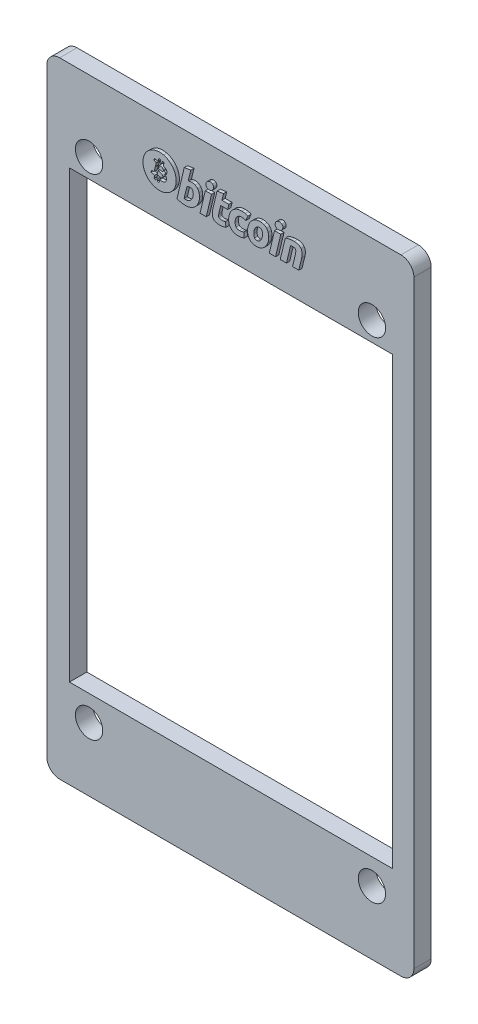
SolidWorks part; units mm, degrees
material "Plastique personnalisé"
ref_plane "Plan de face" through (0, 0, 0) normal (0, 0, 1) x (1, 0, 0)
ref_plane "Plan de dessus" through (0, 0, 0) normal (0, 1, 0) x (1, 0, 0)
ref_plane "Plan de droite" through (0, 0, 0) normal (1, 0, 0) x (0, 0, -1)
sketch "Esquisse1" plane through (0, 0, 0) normal (0, 0, 1) x (1, 0, 0)
  line L1 (-31, -51) -> (26, -51)
  line L2 (-31, -51) -> (-31, 46)
  line L3 (-31, 46) -> (26, 46)
  line L4 (26, -51) -> (26, 46)
  line L5 (-31, -51) -> (26, 46) construction
  line L6 (-31, 46) -> (26, -51) construction
  point P0 (-2.5, -2.5)
  dimension "D1" = 97
  dimension "D2" = 57
extrude "Boss.-Extru.1" add sketch "Esquisse1" along normal blind 2.7
fillet "Congé1" radius 2 4 edges at (-31, -51, 1.35) (26, -51, 1.35) (-31, 46, 1.35) (26, 46, 1.35)
sketch "Esquisse2" plane through (0, 0, 2.7) normal (0, 0, 1) x (1, 0, 0)
  line L1 (-27.4785, 31.965) -> (22.6535, 31.965)
  line L2 (-27.4785, 31.965) -> (-27.4785, -37.1836)
  line L3 (-27.4785, -37.1836) -> (22.6535, -37.1836)
  line L4 (22.6535, 31.965) -> (22.6535, -37.1836)
extrude "Enlèv. mat.-Extru.1" cut sketch "Esquisse2" against normal blind 4
sketch "Esquisse3" plane through (0, 0, 2.7) normal (0, 0, 1) x (1, 0, 0)
  circle A0 centre (-24.4301, 34.9595) radius 2.124
  circle A1 centre (19.4865, 34.9595) radius 2.124
  circle A2 centre (19.4865, -41.1389) radius 2.124
  circle A3 centre (-24.4301, -41.1389) radius 2.124
extrude "Enlèv. mat.-Extru.2" cut sketch "Esquisse3" against normal blind 4
sketch "Esquisse4" plane through (-2.3914, 35.7416, 2.7) normal (0, 0, 1) x (1, 0, 0)
  line L0 (-10.7436, 3.5103) -> (-10.6026, 4.0757)
  line L1 (-10.9703, 2.6018) -> (-10.8147, 3.2251)
  line L2 (-10.0195, 4.2739) -> (-9.9034, 4.739)
  line L3 (-9.9034, 4.739) -> (-10.1866, 4.8096)
  line L4 (-10.1866, 4.8096) -> (-10.2995, 4.3567)
  line L5 (-10.5262, 4.4101) -> (-10.4126, 4.866)
  line L6 (-10.4126, 4.866) -> (-10.6955, 4.9365)
  line L7 (-10.6955, 4.9365) -> (-10.8116, 4.4715)
  line L8 (-10.9924, 4.514) -> (-10.992, 4.5155)
  line L9 (-10.992, 4.5155) -> (-11.3825, 4.613)
  line L10 (-11.3825, 4.613) -> (-11.4578, 4.3106)
  line L11 (-11.1203, 4.0948) -> (-11.2524, 3.5649)
  line L12 (-11.2528, 3.5628) -> (-11.438, 2.8205)
  line L13 (-11.7736, 2.8046) -> (-11.9142, 2.4804)
  line L14 (-11.9142, 2.4804) -> (-11.5457, 2.3885)
  line L15 (-11.3438, 2.3365) -> (-11.4611, 1.866)
  line L16 (-11.4611, 1.866) -> (-11.1782, 1.7954)
  line L17 (-11.1782, 1.7954) -> (-11.0622, 2.261)
  line L18 (-10.8366, 2.2024) -> (-10.9522, 1.7391)
  line L19 (-10.9522, 1.7391) -> (-10.6691, 1.6686)
  line L20 (-10.6691, 1.6686) -> (-10.5519, 2.1381)
  line L21 (-6.3518, 3.2945) -> (-6.7826, 1.5051)
  line L22 (-7.8866, 0.9301) -> (-6.7567, 5.6782)
  line L23 (-6.7567, 5.6782) -> (-5.7446, 5.8351)
  line L24 (-5.7446, 5.8351) -> (-6.1491, 4.1502)
  line L25 (-3.343, 0.7663) -> (-4.3096, 0.7663)
  line L26 (-4.3096, 0.7663) -> (-3.4932, 4.2016)
  line L27 (-3.4932, 4.2016) -> (-2.52, 4.2016)
  line L28 (-2.52, 4.2016) -> (-3.343, 0.7663)
  line L29 (-1.6728, 5.0574) -> (-0.6602, 5.2143)
  line L30 (-0.6602, 5.2143) -> (-0.9089, 4.2017)
  line L31 (-0.9089, 4.2017) -> (0.1754, 4.2017)
  line L32 (0.1754, 4.2017) -> (-0.0204, 3.4051)
  line L33 (-0.0204, 3.4051) -> (-1.0982, 3.4051)
  line L34 (-1.0982, 3.4051) -> (-1.3853, 2.2034)
  line L35 (-0.3667, 1.6092) -> (-0.2945, 0.8644)
  line L36 (-2.3131, 2.3537) -> (-1.6728, 5.0574)
  line L37 (3.1375, 4.0912) -> (2.8042, 3.3331)
  line L38 (2.4909, 1.6348) -> (2.5632, 0.8577)
  line L39 (7.4135, 0.7663) -> (6.4461, 0.7663)
  line L40 (6.4461, 0.7663) -> (7.2624, 4.2016)
  line L41 (7.2624, 4.2016) -> (8.2361, 4.2016)
  line L42 (8.2361, 4.2016) -> (7.4135, 0.7663)
  line L43 (11.4737, 2.6215) -> (11.029, 0.7666)
  line L44 (11.029, 0.7666) -> (10.056, 0.7666)
  line L45 (10.056, 0.7666) -> (10.487, 2.5825)
  line L46 (9.7492, 3.4248) -> (9.1157, 0.7669)
  line L47 (9.1157, 0.7669) -> (8.1422, 0.7669)
  line L48 (8.1422, 0.7669) -> (8.9329, 4.0454)
  spline S0 degree 3 poles (-8.0865, 2.6309) (-8.4311, 1.2483) (-9.8315, 0.4071) (-11.214, 0.7517) knots 0 0 0 0 1 1 1 1
  spline S1 degree 3 poles (-11.214, 0.7517) (-12.5961, 1.0964) (-13.4376, 2.4967) (-13.0927, 3.8791) knots 0 0 0 0 1 1 1 1
  spline S2 degree 3 poles (-13.0927, 3.8791) (-12.7482, 5.2619) (-11.3479, 6.1033) (-9.9657, 5.7586) knots 0 0 0 0 1 1 1 1
  spline S3 degree 3 poles (-9.9657, 5.7586) (-8.5831, 5.4139) (-7.7419, 4.0134) (-8.0865, 2.6309) knots 0 0 0 0 1 1 1 1
  spline S4 degree 3 poles (-10.0112, 3.6278) (-10.091, 3.308) (-10.5838, 3.4705) (-10.7436, 3.5103) knots 0 0 0 0 1 1 1 1
  spline S5 degree 3 poles (-10.6026, 4.0757) (-10.4428, 4.0358) (-9.928, 3.9615) (-10.0112, 3.6278) knots 0 0 0 0 1 1 1 1
  spline S6 degree 3 poles (-10.0987, 2.7157) (-10.1862, 2.3641) (-10.7782, 2.5541) (-10.9703, 2.6018) knots 0 0 0 0 1 1 1 1
  spline S7 degree 3 poles (-10.8147, 3.2251) (-10.6228, 3.1772) (-10.0073, 3.0823) (-10.0987, 2.7157) knots 0 0 0 0 1 1 1 1
  spline S8 degree 3 poles (-9.4518, 3.6228) (-9.4004, 3.9661) (-9.6619, 4.1507) (-10.0195, 4.2739) knots 0 0 0 0 1 1 1 1
  spline S9 degree 3 poles (-10.2995, 4.3567) (-10.3739, 4.3753) (-10.4503, 4.3928) (-10.5262, 4.4101) knots 0 0 0 0 1 1 1 1
  spline S10 degree 3 poles (-10.8116, 4.4715) (-10.8732, 4.4856) (-10.9337, 4.4994) (-10.9924, 4.514) knots 0 0 0 0 1 1 1 1
  spline S11 degree 2 poles (-11.4578, 4.3106) (-11.2478, 4.2624) (-11.2523, 4.2594) knots 0 0 0 1 1 1
  spline S12 degree 3 poles (-11.2523, 4.2594) (-11.1375, 4.2308) (-11.1168, 4.1549) (-11.1203, 4.0948) knots 0 0 0 0 1 1 1 1
  spline S13 degree 3 poles (-11.2524, 3.5649) (-11.2445, 3.5628) (-11.2342, 3.5599) (-11.2229, 3.5554) knots 0 0 0 0 1 1 1 1
  spline S14 degree 3 poles (-11.2229, 3.5554) (-11.2324, 3.5578) (-11.2425, 3.5603) (-11.2528, 3.5628) knots 0 0 0 0 1 1 1 1
  spline S15 degree 3 poles (-11.438, 2.8205) (-11.452, 2.7857) (-11.4877, 2.7335) (-11.5678, 2.7532) knots 0 0 0 0 1 1 1 1
  spline S16 degree 2 poles (-11.5678, 2.7532) (-11.565, 2.7491) (-11.7736, 2.8046) knots 0 0 0 1 1 1
  spline S17 degree 3 poles (-11.5457, 2.3885) (-11.4772, 2.3713) (-11.41, 2.3534) (-11.3438, 2.3365) knots 0 0 0 0 1 1 1 1
  spline S18 degree 3 poles (-11.0622, 2.261) (-10.9849, 2.24) (-10.91, 2.2207) (-10.8366, 2.2024) knots 0 0 0 0 1 1 1 1
  spline S19 degree 3 poles (-10.5519, 2.1381) (-10.0691, 2.0467) (-9.706, 2.0836) (-9.5532, 2.5202) knots 0 0 0 0 1 1 1 1
  spline S20 degree 3 poles (-9.5532, 2.5202) (-9.43, 2.8718) (-9.5593, 3.0746) (-9.8133, 3.207) knots 0 0 0 0 1 1 1 1
  spline S21 degree 3 poles (-9.8133, 3.207) (-9.6283, 3.2497) (-9.489, 3.3714) (-9.4518, 3.6228) knots 0 0 0 0 1 1 1 1
  spline S22 degree 3 poles (-6.4564, 1.4784) (-6.304, 1.4784) (-6.1603, 1.5159) (-6.0254, 1.5895) knots 0 0 0 0 1 1 1 1
  spline S23 degree 3 poles (-6.0254, 1.5895) (-5.8902, 1.6632) (-5.7733, 1.7627) (-5.6755, 1.8866) knots 0 0 0 0 1 1 1 1
  spline S24 degree 3 poles (-5.6755, 1.8866) (-5.5777, 2.0112) (-5.5003, 2.1515) (-5.4438, 2.3083) knots 0 0 0 0 1 1 1 1
  spline S25 degree 3 poles (-5.4438, 2.3083) (-5.3874, 2.4649) (-5.3589, 2.6283) (-5.3589, 2.7983) knots 0 0 0 0 1 1 1 1
  spline S26 degree 3 poles (-5.3589, 2.7983) (-5.3589, 3.0074) (-5.3937, 3.1703) (-5.4634, 3.2882) knots 0 0 0 0 1 1 1 1
  spline S27 degree 3 poles (-5.4634, 3.2882) (-5.533, 3.4055) (-5.6617, 3.4645) (-5.8487, 3.4645) knots 0 0 0 0 1 1 1 1
  spline S28 degree 3 poles (-5.8487, 3.4645) (-5.9101, 3.4645) (-5.989, 3.4528) (-6.0869, 3.432) knots 0 0 0 0 1 1 1 1
  spline S29 degree 3 poles (-6.0869, 3.432) (-6.1852, 3.4098) (-6.2731, 3.3637) (-6.3518, 3.2945) knots 0 0 0 0 1 1 1 1
  spline S30 degree 3 poles (-6.7826, 1.5051) (-6.7567, 1.5004) (-6.7337, 1.4962) (-6.7141, 1.492) knots 0 0 0 0 1 1 1 1
  spline S31 degree 3 poles (-6.7141, 1.492) (-6.6949, 1.4875) (-6.6737, 1.4844) (-6.6526, 1.4823) knots 0 0 0 0 1 1 1 1
  spline S32 degree 3 poles (-6.6526, 1.4823) (-6.6302, 1.4798) (-6.6046, 1.4785) (-6.5737, 1.4785) knots 0 0 0 0 1 1 1 1
  spline S33 degree 3 poles (-6.5737, 1.4785) (-6.5428, 1.4785) (-6.5043, 1.4784) (-6.4564, 1.4784) knots 0 0 0 0 1 1 1 1
  spline S34 degree 3 poles (-5.6075, 4.2744) (-5.3982, 4.2744) (-5.2174, 4.2369) (-5.0654, 4.1632) knots 0 0 0 0 1 1 1 1
  spline S35 degree 3 poles (-5.0654, 4.1632) (-4.9128, 4.0889) (-4.7868, 3.9887) (-4.6858, 3.8628) knots 0 0 0 0 1 1 1 1
  spline S36 degree 3 poles (-4.6858, 3.8628) (-4.5862, 3.7362) (-4.512, 3.5882) (-4.464, 3.4186) knots 0 0 0 0 1 1 1 1
  spline S37 degree 3 poles (-4.464, 3.4186) (-4.4164, 3.2485) (-4.3925, 3.0657) (-4.3925, 2.87) knots 0 0 0 0 1 1 1 1
  spline S38 degree 3 poles (-4.3925, 2.87) (-4.3925, 2.5693) (-4.4476, 2.2853) (-4.5589, 2.0176) knots 0 0 0 0 1 1 1 1
  spline S39 degree 3 poles (-4.5589, 2.0176) (-4.6701, 1.7495) (-4.821, 1.5169) (-5.0129, 1.3184) knots 0 0 0 0 1 1 1 1
  spline S40 degree 3 poles (-5.0129, 1.3184) (-5.2047, 1.1203) (-5.4311, 0.9641) (-5.6922, 0.8487) knots 0 0 0 0 1 1 1 1
  spline S41 degree 3 poles (-5.6922, 0.8487) (-5.9529, 0.7333) (-6.2364, 0.6755) (-6.5408, 0.6755) knots 0 0 0 0 1 1 1 1
  spline S42 degree 3 poles (-6.5408, 0.6755) (-6.5801, 0.6755) (-6.6494, 0.6766) (-6.747, 0.6787) knots 0 0 0 0 1 1 1 1
  spline S43 degree 3 poles (-6.747, 0.6787) (-6.8448, 0.6806) (-6.9571, 0.6907) (-7.083, 0.7077) knots 0 0 0 0 1 1 1 1
  spline S44 degree 3 poles (-7.083, 0.7077) (-7.2095, 0.7254) (-7.3434, 0.7515) (-7.4848, 0.7866) knots 0 0 0 0 1 1 1 1
  spline S45 degree 3 poles (-7.4848, 0.7866) (-7.6261, 0.8209) (-7.7603, 0.869) (-7.8866, 0.9301) knots 0 0 0 0 1 1 1 1
  spline S46 degree 3 poles (-6.1491, 4.1502) (-6.0625, 4.1892) (-5.9753, 4.2195) (-5.8882, 4.2415) knots 0 0 0 0 1 1 1 1
  spline S47 degree 3 poles (-5.8882, 4.2415) (-5.801, 4.2631) (-5.7074, 4.2744) (-5.6075, 4.2744) knots 0 0 0 0 1 1 1 1
  spline S48 degree 3 poles (-2.8726, 4.6201) (-3.0075, 4.6201) (-3.1297, 4.6603) (-3.2384, 4.7408) knots 0 0 0 0 1 1 1 1
  spline S49 degree 3 poles (-3.2384, 4.7408) (-3.3478, 4.8208) (-3.4019, 4.9439) (-3.4019, 5.1099) knots 0 0 0 0 1 1 1 1
  spline S50 degree 3 poles (-3.4019, 5.1099) (-3.4019, 5.2012) (-3.3835, 5.2868) (-3.3467, 5.3676) knots 0 0 0 0 1 1 1 1
  spline S51 degree 3 poles (-3.3467, 5.3676) (-3.3093, 5.4483) (-3.2606, 5.5177) (-3.1994, 5.5767) knots 0 0 0 0 1 1 1 1
  spline S52 degree 3 poles (-3.1994, 5.5767) (-3.1384, 5.6353) (-3.0677, 5.682) (-2.9873, 5.7172) knots 0 0 0 0 1 1 1 1
  spline S53 degree 3 poles (-2.9873, 5.7172) (-2.9065, 5.752) (-2.8205, 5.7694) (-2.7289, 5.7694) knots 0 0 0 0 1 1 1 1
  spline S54 degree 3 poles (-2.7289, 5.7694) (-2.5941, 5.7694) (-2.4724, 5.7292) (-2.3635, 5.6487) knots 0 0 0 0 1 1 1 1
  spline S55 degree 3 poles (-2.3635, 5.6487) (-2.2549, 5.5679) (-2.2003, 5.4447) (-2.2003, 5.2796) knots 0 0 0 0 1 1 1 1
  spline S56 degree 3 poles (-2.2003, 5.2796) (-2.2003, 5.188) (-2.2188, 5.102) (-2.2559, 5.0214) knots 0 0 0 0 1 1 1 1
  spline S57 degree 3 poles (-2.2559, 5.0214) (-2.2927, 4.9408) (-2.3415, 4.8713) (-2.4027, 4.8123) knots 0 0 0 0 1 1 1 1
  spline S58 degree 3 poles (-2.4027, 4.8123) (-2.4632, 4.7537) (-2.5346, 4.707) (-2.6147, 4.6721) knots 0 0 0 0 1 1 1 1
  spline S59 degree 3 poles (-2.6147, 4.6721) (-2.6956, 4.6368) (-2.7813, 4.6201) (-2.8726, 4.6201) knots 0 0 0 0 1 1 1 1
  spline S60 degree 3 poles (-1.3853, 2.2034) (-1.4118, 2.1034) (-1.4267, 2.0099) (-1.431, 1.9229) knots 0 0 0 0 1 1 1 1
  spline S61 degree 3 poles (-1.431, 1.9229) (-1.4357, 1.8355) (-1.4247, 1.7605) (-1.3986, 1.6974) knots 0 0 0 0 1 1 1 1
  spline S62 degree 3 poles (-1.3986, 1.6974) (-1.3725, 1.6341) (-1.3258, 1.5852) (-1.2581, 1.5509) knots 0 0 0 0 1 1 1 1
  spline S63 degree 3 poles (-1.2581, 1.5509) (-1.1906, 1.5157) (-1.0941, 1.4981) (-0.9676, 1.4981) knots 0 0 0 0 1 1 1 1
  spline S64 degree 3 poles (-0.9676, 1.4981) (-0.8633, 1.4981) (-0.7616, 1.508) (-0.6634, 1.5277) knots 0 0 0 0 1 1 1 1
  spline S65 degree 3 poles (-0.6634, 1.5277) (-0.5657, 1.547) (-0.4669, 1.5739) (-0.3667, 1.6092) knots 0 0 0 0 1 1 1 1
  spline S66 degree 3 poles (-0.2945, 0.8644) (-0.425, 0.8165) (-0.5665, 0.7753) (-0.719, 0.7406) knots 0 0 0 0 1 1 1 1
  spline S67 degree 3 poles (-0.719, 0.7406) (-0.8716, 0.7054) (-1.0524, 0.6886) (-1.2612, 0.6886) knots 0 0 0 0 1 1 1 1
  spline S68 degree 3 poles (-1.2612, 0.6886) (-1.5616, 0.6886) (-1.7944, 0.7332) (-1.9602, 0.8219) knots 0 0 0 0 1 1 1 1
  spline S69 degree 3 poles (-1.9602, 0.8219) (-2.126, 0.9112) (-2.243, 1.0335) (-2.3131, 1.1882) knots 0 0 0 0 1 1 1 1
  spline S70 degree 3 poles (-2.3131, 1.1882) (-2.3823, 1.3422) (-2.4131, 1.5199) (-2.4044, 1.7201) knots 0 0 0 0 1 1 1 1
  spline S71 degree 3 poles (-2.4044, 1.7201) (-2.3956, 1.9207) (-2.3653, 2.1317) (-2.3131, 2.3537) knots 0 0 0 0 1 1 1 1
  spline S72 degree 3 poles (0.1329, 2.138) (0.1329, 2.434) (0.1808, 2.7129) (0.2765, 2.9742) knots 0 0 0 0 1 1 1 1
  spline S73 degree 3 poles (0.2765, 2.9742) (0.3721, 3.2356) (0.5097, 3.4643) (0.6883, 3.6604) knots 0 0 0 0 1 1 1 1
  spline S74 degree 3 poles (0.6883, 3.6604) (0.8663, 3.8556) (1.083, 4.0103) (1.3383, 4.1239) knots 0 0 0 0 1 1 1 1
  spline S75 degree 3 poles (1.3383, 4.1239) (1.5923, 4.2368) (1.8768, 4.2937) (2.1902, 4.2937) knots 0 0 0 0 1 1 1 1
  spline S76 degree 3 poles (2.1902, 4.2937) (2.3864, 4.2937) (2.5617, 4.2752) (2.7159, 4.238) knots 0 0 0 0 1 1 1 1
  spline S77 degree 3 poles (2.7159, 4.238) (2.8708, 4.2005) (3.0108, 4.152) (3.1375, 4.0912) knots 0 0 0 0 1 1 1 1
  spline S78 degree 3 poles (2.8042, 3.3331) (2.7171, 3.3685) (2.6267, 3.3996) (2.5332, 3.4278) knots 0 0 0 0 1 1 1 1
  spline S79 degree 3 poles (2.5332, 3.4278) (2.4397, 3.4566) (2.3254, 3.4705) (2.1904, 3.4705) knots 0 0 0 0 1 1 1 1
  spline S80 degree 3 poles (2.1904, 3.4705) (1.8677, 3.4705) (1.6127, 3.3593) (1.4229, 3.1377) knots 0 0 0 0 1 1 1 1
  spline S81 degree 3 poles (1.4229, 3.1377) (1.2336, 2.9157) (1.1384, 2.617) (1.1384, 2.2425) knots 0 0 0 0 1 1 1 1
  spline S82 degree 3 poles (1.1384, 2.2425) (1.1384, 2.0204) (1.1864, 1.841) (1.2825, 1.7036) knots 0 0 0 0 1 1 1 1
  spline S83 degree 3 poles (1.2825, 1.7036) (1.3781, 1.5663) (1.5549, 1.4979) (1.8113, 1.4979) knots 0 0 0 0 1 1 1 1
  spline S84 degree 3 poles (1.8113, 1.4979) (1.9379, 1.4979) (2.0601, 1.5112) (2.1772, 1.5369) knots 0 0 0 0 1 1 1 1
  spline S85 degree 3 poles (2.1772, 1.5369) (2.2951, 1.5631) (2.3992, 1.596) (2.4909, 1.6348) knots 0 0 0 0 1 1 1 1
  spline S86 degree 3 poles (2.5632, 0.8577) (2.4409, 0.8103) (2.306, 0.7675) (2.1582, 0.73) knots 0 0 0 0 1 1 1 1
  spline S87 degree 3 poles (2.1582, 0.73) (2.0099, 0.6938) (1.8335, 0.6749) (1.6289, 0.6749) knots 0 0 0 0 1 1 1 1
  spline S88 degree 3 poles (1.6289, 0.6749) (1.3589, 0.6749) (1.1302, 0.7145) (0.9433, 0.7923) knots 0 0 0 0 1 1 1 1
  spline S89 degree 3 poles (0.9433, 0.7923) (0.7562, 0.8713) (0.6016, 0.9763) (0.4797, 1.1091) knots 0 0 0 0 1 1 1 1
  spline S90 degree 3 poles (0.4797, 1.1091) (0.3572, 1.2423) (0.2694, 1.398) (0.2151, 1.5765) knots 0 0 0 0 1 1 1 1
  spline S91 degree 3 poles (0.2151, 1.5765) (0.1608, 1.7549) (0.1329, 1.9426) (0.1329, 2.138) knots 0 0 0 0 1 1 1 1
  spline S92 degree 3 poles (4.9103, 3.4705) (4.7671, 3.4705) (4.6403, 3.4289) (4.5319, 3.3467) knots 0 0 0 0 1 1 1 1
  spline S93 degree 3 poles (4.5319, 3.3467) (4.423, 3.2635) (4.3316, 3.159) (4.2579, 3.0331) knots 0 0 0 0 1 1 1 1
  spline S94 degree 3 poles (4.2579, 3.0331) (4.1834, 2.9064) (4.1283, 2.7682) (4.0909, 2.6182) knots 0 0 0 0 1 1 1 1
  spline S95 degree 3 poles (4.0909, 2.6182) (4.0539, 2.4678) (4.0356, 2.3256) (4.0356, 2.1905) knots 0 0 0 0 1 1 1 1
  spline S96 degree 3 poles (4.0356, 2.1905) (4.0356, 1.9726) (4.0709, 1.8027) (4.1399, 1.6806) knots 0 0 0 0 1 1 1 1
  spline S97 degree 3 poles (4.1399, 1.6806) (4.2099, 1.5591) (4.336, 1.498) (4.5188, 1.498) knots 0 0 0 0 1 1 1 1
  spline S98 degree 3 poles (4.5188, 1.498) (4.6626, 1.498) (4.7887, 1.5393) (4.8978, 1.6223) knots 0 0 0 0 1 1 1 1
  spline S99 degree 3 poles (4.8978, 1.6223) (5.006, 1.7048) (5.0976, 1.8094) (5.1718, 1.9357) knots 0 0 0 0 1 1 1 1
  spline S100 degree 3 poles (5.1718, 1.9357) (5.2458, 2.0616) (5.3016, 2.2002) (5.3388, 2.3505) knots 0 0 0 0 1 1 1 1
  spline S101 degree 3 poles (5.3388, 2.3505) (5.3755, 2.5004) (5.394, 2.6434) (5.394, 2.7782) knots 0 0 0 0 1 1 1 1
  spline S102 degree 3 poles (5.394, 2.7782) (5.394, 2.9956) (5.359, 3.1658) (5.2893, 3.2878) knots 0 0 0 0 1 1 1 1
  spline S103 degree 3 poles (5.2893, 3.2878) (5.2197, 3.4094) (5.0932, 3.4705) (4.9103, 3.4705) knots 0 0 0 0 1 1 1 1
  spline S104 degree 3 poles (4.4273, 0.6752) (4.1965, 0.6752) (3.996, 0.7104) (3.8261, 0.78) knots 0 0 0 0 1 1 1 1
  spline S105 degree 3 poles (3.8261, 0.78) (3.6565, 0.8495) (3.5163, 0.9473) (3.4052, 1.074) knots 0 0 0 0 1 1 1 1
  spline S106 degree 3 poles (3.4052, 1.074) (3.2939, 1.1998) (3.2107, 1.3491) (3.1537, 1.5211) knots 0 0 0 0 1 1 1 1
  spline S107 degree 3 poles (3.1537, 1.5211) (3.0967, 1.6931) (3.0693, 1.8836) (3.0693, 2.0921) knots 0 0 0 0 1 1 1 1
  spline S108 degree 3 poles (3.0693, 2.0921) (3.0693, 2.3537) (3.1112, 2.6153) (3.1961, 2.8764) knots 0 0 0 0 1 1 1 1
  spline S109 degree 3 poles (3.1961, 2.8764) (3.2808, 3.1378) (3.4062, 3.3727) (3.572, 3.5815) knots 0 0 0 0 1 1 1 1
  spline S110 degree 3 poles (3.572, 3.5815) (3.7367, 3.7906) (3.94, 3.9615) (4.179, 4.0948) knots 0 0 0 0 1 1 1 1
  spline S111 degree 3 poles (4.179, 4.0948) (4.418, 4.2273) (4.6928, 4.2939) (5.0015, 4.2939) knots 0 0 0 0 1 1 1 1
  spline S112 degree 3 poles (5.0015, 4.2939) (5.228, 4.2939) (5.4273, 4.2586) (5.5997, 4.189) knots 0 0 0 0 1 1 1 1
  spline S113 degree 3 poles (5.5997, 4.189) (5.7713, 4.1196) (5.9126, 4.0211) (6.0242, 3.8952) knots 0 0 0 0 1 1 1 1
  spline S114 degree 3 poles (6.0242, 3.8952) (6.1348, 3.7685) (6.2188, 3.6199) (6.2751, 3.4477) knots 0 0 0 0 1 1 1 1
  spline S115 degree 3 poles (6.2751, 3.4477) (6.332, 3.276) (6.3601, 3.0852) (6.3601, 2.8764) knots 0 0 0 0 1 1 1 1
  spline S116 degree 3 poles (6.3601, 2.8764) (6.3601, 2.6156) (6.3186, 2.3539) (6.2363, 2.0923) knots 0 0 0 0 1 1 1 1
  spline S117 degree 3 poles (6.2363, 2.0923) (6.1541, 1.8318) (6.0318, 1.5963) (5.8705, 1.3871) knots 0 0 0 0 1 1 1 1
  spline S118 degree 3 poles (5.8705, 1.3871) (5.7096, 1.1782) (5.5084, 1.0073) (5.2666, 0.8746) knots 0 0 0 0 1 1 1 1
  spline S119 degree 3 poles (5.2666, 0.8746) (5.0252, 0.7418) (4.7451, 0.6752) (4.4273, 0.6752) knots 0 0 0 0 1 1 1 1
  spline S120 degree 3 poles (7.8831, 4.6201) (7.7483, 4.6201) (7.626, 4.6603) (7.5177, 4.7408) knots 0 0 0 0 1 1 1 1
  spline S121 degree 3 poles (7.5177, 4.7408) (7.4087, 4.8208) (7.3541, 4.9439) (7.3541, 5.1099) knots 0 0 0 0 1 1 1 1
  spline S122 degree 3 poles (7.3541, 5.1099) (7.3541, 5.2012) (7.3729, 5.2868) (7.4098, 5.3676) knots 0 0 0 0 1 1 1 1
  spline S123 degree 3 poles (7.4098, 5.3676) (7.4466, 5.4483) (7.4956, 5.5177) (7.5568, 5.5767) knots 0 0 0 0 1 1 1 1
  spline S124 degree 3 poles (7.5568, 5.5767) (7.6176, 5.6353) (7.6889, 5.682) (7.7691, 5.7172) knots 0 0 0 0 1 1 1 1
  spline S125 degree 3 poles (7.7691, 5.7172) (7.8494, 5.752) (7.9354, 5.7694) (8.0266, 5.7694) knots 0 0 0 0 1 1 1 1
  spline S126 degree 3 poles (8.0266, 5.7694) (8.1619, 5.7694) (8.2839, 5.7292) (8.3927, 5.6487) knots 0 0 0 0 1 1 1 1
  spline S127 degree 3 poles (8.3927, 5.6487) (8.5014, 5.5679) (8.5563, 5.4447) (8.5563, 5.2796) knots 0 0 0 0 1 1 1 1
  spline S128 degree 3 poles (8.5563, 5.2796) (8.5563, 5.188) (8.5368, 5.102) (8.5002, 5.0214) knots 0 0 0 0 1 1 1 1
  spline S129 degree 3 poles (8.5002, 5.0214) (8.4637, 4.9408) (8.4146, 4.8713) (8.3538, 4.8123) knots 0 0 0 0 1 1 1 1
  spline S130 degree 3 poles (8.3538, 4.8123) (8.2925, 4.7537) (8.2219, 4.707) (8.1417, 4.6721) knots 0 0 0 0 1 1 1 1
  spline S131 degree 3 poles (8.1417, 4.6721) (8.0606, 4.6368) (7.975, 4.6201) (7.8831, 4.6201) knots 0 0 0 0 1 1 1 1
  spline S132 degree 3 poles (8.9329, 4.0454) (9.0062, 4.0668) (9.0882, 4.0926) (9.1772, 4.1207) knots 0 0 0 0 1 1 1 1
  spline S133 degree 3 poles (9.1772, 4.1207) (9.2667, 4.1487) (9.3667, 4.1748) (9.4783, 4.1983) knots 0 0 0 0 1 1 1 1
  spline S134 degree 3 poles (9.4783, 4.1983) (9.5887, 4.2227) (9.7133, 4.2424) (9.8503, 4.2576) knots 0 0 0 0 1 1 1 1
  spline S135 degree 3 poles (9.8503, 4.2576) (9.9871, 4.2732) (10.1434, 4.2808) (10.3167, 4.2808) knots 0 0 0 0 1 1 1 1
  spline S136 degree 3 poles (10.3167, 4.2808) (10.8266, 4.2808) (11.1781, 4.1323) (11.3721, 3.8362) knots 0 0 0 0 1 1 1 1
  spline S137 degree 3 poles (11.3721, 3.8362) (11.5659, 3.5402) (11.5995, 3.1351) (11.4737, 2.6215) knots 0 0 0 0 1 1 1 1
  spline S138 degree 3 poles (10.487, 2.5825) (10.5133, 2.6958) (10.5339, 2.8055) (10.5492, 2.9125) knots 0 0 0 0 1 1 1 1
  spline S139 degree 3 poles (10.5492, 2.9125) (10.5646, 3.0187) (10.5637, 3.1124) (10.5457, 3.1933) knots 0 0 0 0 1 1 1 1
  spline S140 degree 3 poles (10.5457, 3.1933) (10.5285, 3.2733) (10.488, 3.3387) (10.4253, 3.3895) knots 0 0 0 0 1 1 1 1
  spline S141 degree 3 poles (10.4253, 3.3895) (10.3615, 3.4394) (10.2651, 3.4645) (10.1344, 3.4645) knots 0 0 0 0 1 1 1 1
  spline S142 degree 3 poles (10.1344, 3.4645) (10.0084, 3.4645) (9.8801, 3.4509) (9.7492, 3.4248) knots 0 0 0 0 1 1 1 1
extrude "Boss.-Extru.2" add sketch "Esquisse4" along normal blind 0.5 contours S3 S2 S1 S0 S21 S20 S19 L20 L19 L18 S18 L17 L16 L15 S17 L14 L13 S16 S15 L12 S14 S13 L11 S12 S11 L10 L9 L8 S10 L7 L6 L5 S9 L4 L3 L2 S8 | S5 L0 S4 | S7 L1 S6 | S47 S46 L24 L23 L22 S45 S44 S43 S42 S41 S40 S39 S38 S37 S36 S35 S34 S33 S32 S31 S30 L21 S29 S28 S27 S26 S25 S24 S23 S22 | L28 L27 L26 L25 | S59 S58 S57 S56 S55 S54 S53 S52 S51 S50 S49 S48 | S71 S70 S69 S68 S67 S66 L35 S65 S64 S63 S62 S61 S60 L34 L33 L32 L31 L30 L29 L36 | S91 S90 S89 S88 S87 S86 L38 S85 S84 S83 S82 S81 S80 S79 S78 L37 S77 S76 S75 S74 S73 S72 | S119 S118 S117 S116 S115 S114 S113 S112 S111 S110 S109 S108 S107 S106 S105 S104 S103 S102 S101 S100 S99 S98 S97 S96 S95 S94 S93 S92 | L42 L41 L40 L39 | S131 S130 S129 S128 S127 S126 S125 S124 S123 S122 S121 S120 | S142 S141 S140 S139 S138 L45 L44 L43 S137 S136 S135 S134 S133 S132 L48 L47 L46
